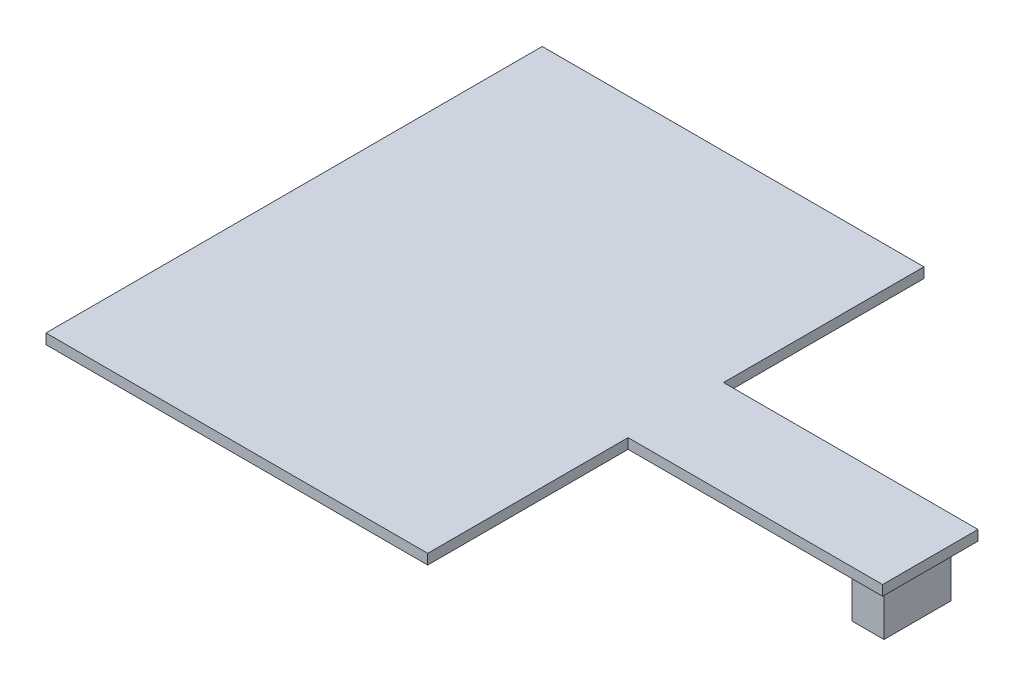
SolidWorks part; units mm, degrees
ref_plane "Front Plane" through (0, 0, 0) normal (0, 0, 1) x (1, 0, 0)
ref_plane "Top Plane" through (0, 0, 0) normal (0, 1, 0) x (1, 0, 0)
ref_plane "Right Plane" through (0, 0, 0) normal (1, 0, 0) x (0, 0, -1)
sketch "Sketch1" plane through (0, 0, 0) normal (0, 1, 0) x (1, 0, 0)
  line L0 (-55, 0) -> (55, 0) construction
  line L1 (-30, -39) -> (30, -39)
  line L2 (-30, -39) -> (-30, 39)
  line L3 (-30, 39) -> (30, 39)
  line L4 (30, -39) -> (30, 39)
  line L5 (-30, -39) -> (30, 39) construction
  line L6 (-30, 39) -> (30, -39) construction
  line L7 (70, -7.5) -> (30, -7.5)
  line L8 (70, -7.5) -> (70, 7.5)
  line L9 (70, 7.5) -> (30, 7.5)
  line L10 (30, -7.5) -> (30, 7.5)
  line L11 (70, -7.5) -> (30, 7.5) construction
  line L12 (70, 7.5) -> (30, -7.5) construction
  point P0 (0, 0)
  point P5 (50, 0)
  dimension "D1" = 60
  dimension "D2" = 78
  dimension "D3" = 15
  dimension "D4" = 40
extrude "Boss-Extrude1" add sketch "Sketch1" against normal blind 1.6 contours L1 L4 L3 L2 | L8 L9 L4 L7
sketch "Sketch2" plane through (0, -1.6, 0) normal (0, -1, 0) x (1, 0, 0)
  line L0 (55, 0) -> (-55, 0) construction
  line L1 (63, -5.28) -> (68, -5.28)
  line L2 (63, -5.28) -> (63, 5.28)
  line L3 (63, 5.28) -> (68, 5.28)
  line L4 (68, -5.28) -> (68, 5.28)
  line L5 (63, -5.28) -> (68, 5.28) construction
  line L6 (63, 5.28) -> (68, -5.28) construction
  line L7 (70, 7.5) -> (70, -7.5) construction
  point P0 (65.5, 0)
  dimension "D1" = 10.56
  dimension "D2" = 5
  dimension "D3" = 2
extrude "Boss-Extrude2" add sketch "Sketch2" along normal blind 8
